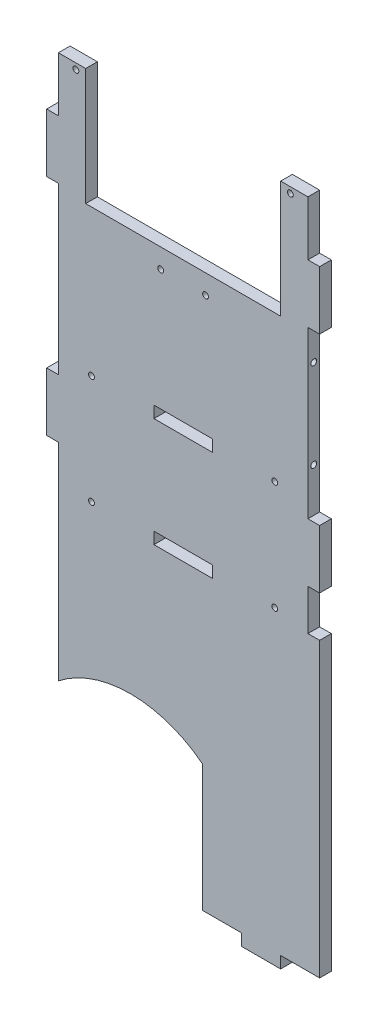
SolidWorks part; units mm, degrees
ref_plane "Plan de face" through (0, 0, 0) normal (0, 0, 1) x (1, 0, 0)
ref_plane "Plan de dessus" through (0, 0, 0) normal (0, 1, 0) x (1, 0, 0)
ref_plane "Plan de droite" through (0, 0, 0) normal (1, 0, 0) x (0, 0, -1)
sketch "Esquisse1" plane through (0, 0, 0) normal (0, 0, 1) x (1, 0, 0)
  line L0 (16.4964, 165.4872) -> (16.4964, 162.4872) construction
  line L1 (-0.0036, 165.4872) -> (139.9964, 165.4872)
  line L2 (-0.0036, 165.4872) -> (-0.0036, -184.5128)
  line L3 (-0.0036, -184.5128) -> (139.9964, -184.5128)
  line L4 (139.9964, 165.4872) -> (139.9964, -184.5128)
  line L5 (54.9964, -22.5128) -> (84.9964, -22.5128)
  line L6 (54.9964, -22.5128) -> (54.9964, -28.5128)
  line L7 (54.9964, -28.5128) -> (84.9964, -28.5128)
  line L8 (84.9964, -22.5128) -> (84.9964, -28.5128)
  line L9 (19.9964, 165.4872) -> (119.9964, 165.4872)
  line L11 (19.9964, 165.4872) -> (119.9964, 165.4872)
  line L12 (19.9964, 165.4872) -> (19.9964, 105.4872)
  line L13 (69.9964, 165.4872) -> (69.9964, -184.5128) construction
  line L18 (19.9964, 105.4872) -> (119.9964, 105.4872)
  line L19 (119.9964, 165.4872) -> (119.9964, 105.4872)
  circle A0 centre (14.9964, 162.4872) radius 1.5
  circle A1 centre (124.9964, 162.4872) radius 1.5
  circle A2 centre (69.9964, 162.3872) radius 3
  circle A5 centre (58.4964, 95.4872) radius 1.5
  circle A6 centre (22.9964, -25.5128) radius 1.5
  circle A7 centre (116.9964, -25.5128) radius 1.5
  circle A8 centre (81.4964, 95.4872) radius 1.5
  dimension "D3" = 3
  dimension "D6" = 60
  dimension "D9" = 10
  dimension "D23" = 11.5
  dimension "D24" = 3
  dimension "D25" = 3
  dimension "D27" = 3
  dimension "D28" = 3
  dimension "D1" = 140
  dimension "D2" = 350
  dimension "D4" = 15
  dimension "D5" = 15
  dimension "D7" = 100
  dimension "D8" = 5
  dimension "D11" = 3
  dimension "D12" = 23
  dimension "D13" = 23
  dimension "D14" = 156
  dimension "D15" = 6
  dimension "D16" = 55
  dimension "D17" = 30
  dimension "D29" = 3
  dimension "D31" = 3
sketch "Esquisse4" plane through (0, 0, 0) normal (0, 0, 1) x (1, 0, 0)
  line L0 (-0.0036, 165.4872) -> (-0.0036, -184.5128) construction
  line L1 (-0.0036, 165.4872) -> (5.9964, 165.4872)
  line L2 (-0.0036, 165.4872) -> (-0.0036, 137.4872)
  line L3 (-0.0036, 137.4872) -> (5.9964, 137.4872)
  line L4 (5.9964, 165.4872) -> (5.9964, 137.4872)
  line L5 (-0.0036, 107.4872) -> (5.9964, 107.4872)
  line L6 (-0.0036, 107.4872) -> (-0.0036, 22.4872)
  line L7 (-0.0036, 22.4872) -> (5.9964, 22.4872)
  line L8 (5.9964, 107.4872) -> (5.9964, 22.4872)
  line L9 (69.9964, 162.3872) -> (69.9964, -184.5128) construction
  line L10 (-0.0036, -7.5128) -> (5.9964, -7.5128)
  line L11 (-0.0036, -7.5128) -> (-0.0036, -58.5128)
  line L12 (-0.0036, -58.5128) -> (5.9964, -58.5128)
  line L13 (5.9964, -7.5128) -> (5.9964, -58.5128)
  line L14 (-0.0036, -184.5128) -> (139.9964, -184.5128) construction
  line L15 (139.9964, -7.5128) -> (133.9964, -7.5128)
  line L16 (133.9964, -7.5128) -> (133.9964, -28.5128)
  line L17 (133.9964, -28.5128) -> (139.9964, -28.5128)
  line L18 (139.9964, -28.5128) -> (139.9964, -7.5128)
  line L19 (139.9964, 22.4872) -> (133.9964, 22.4872)
  line L20 (139.9964, 107.4872) -> (139.9964, 22.4872)
  line L21 (133.9964, 107.4872) -> (133.9964, 22.4872)
  line L22 (139.9964, 107.4872) -> (133.9964, 107.4872)
  line L23 (139.9964, 165.4872) -> (133.9964, 165.4872)
  line L24 (139.9964, 137.4872) -> (133.9964, 137.4872)
  line L25 (139.9964, 165.4872) -> (139.9964, 137.4872)
  line L26 (133.9964, 165.4872) -> (133.9964, 137.4872)
  line L27 (139.9964, 165.4872) -> (139.9964, -222.3339) construction
  line L28 (190.2583, -184.5128) -> (43.4436, -184.5128) construction
  dimension "D1" = 6
  dimension "D2" = 28
  dimension "D3" = 30
  dimension "D4" = 85
  dimension "D5" = 30
  dimension "D6" = 51
  dimension "D7" = 21
  dimension "D8" = 30
  dimension "D9" = 6
extrude "Boss.-Extru.3" add sketch "Esquisse1" along normal blind 6
extrude "Enlèv. mat.-Extru.2" cut sketch "Esquisse4" along normal blind 6
sketch "Esquisse5" plane through (0, 0, 0) normal (1, 0, 0) x (0, 0, -1)
  line L0 (0, -125.6726) -> (0, 121.1593) construction
  line L1 (0, 121.1593) -> (0, 30.1192) construction
  line L2 (-6, -7.5128) -> (0, -7.5128) construction
  line L3 (-6, 22.4872) -> (0, 22.4872) construction
  line L4 (-6, 107.4872) -> (0, 107.4872) construction
  line L5 (-6, 137.4872) -> (0, 137.4872) construction
  circle A0 centre (-3, -30.0128) radius 1.5
  circle A1 centre (-3, -0.0128) radius 1.5
  circle A2 centre (-3, 90.4872) radius 1.5
  circle A3 centre (-3, 120.4872) radius 1.5
  point P5 (-3, -7.5128)
  point P11 (-3, 22.4872)
  point P20 (-3, 137.4872)
  dimension "D1" = 3
  dimension "D2" = 22.5
  dimension "D3" = 22.5
  dimension "D4" = 17
  dimension "D5" = 17
sketch "Esquisse6" plane through (133.9964, 0, 0) normal (1, 0, 0) x (0, 0, -1)
  line L0 (-6, 107.4872) -> (0, 107.4872) construction
  line L1 (-6, 107.4872) -> (-6, 22.4872) construction
  line L2 (-6, 22.4872) -> (0, 22.4872) construction
  line L3 (-3, 90.4872) -> (-3, 44.9872) construction
  line L5 (-6, 137.4872) -> (0, 137.4872) construction
  circle A0 centre (-3, 90.4872) radius 1.5
  circle A1 centre (-3, 44.9872) radius 1.5
  circle A3 centre (-3, 120.4872) radius 1.5
  point P8 (-3, 22.4872)
  point P17 (-3, 137.4872)
  dimension "D1" = 17
  dimension "D3" = 22.5
  dimension "D5" = 17
  dimension "D2" = 3
extrude "Enlèv. mat.-Extru.3" cut sketch "Esquisse5" along normal blind 9
extrude "Enlèv. mat.-Extru.6" cut sketch "Esquisse6" against normal blind 3
sketch "Esquisse7" plane through (0, 0, 0) normal (0, 0, 1) x (1, 0, 0)
  line L0 (-0.0036, -184.5128) -> (139.9964, -184.5128) construction
  line L1 (139.9964, -184.5128) -> (119.9964, -184.5128)
  line L2 (139.9964, -184.5128) -> (139.9964, -178.5128)
  line L3 (139.9964, -178.5128) -> (119.9964, -178.5128)
  line L4 (119.9964, -184.5128) -> (119.9964, -178.5128)
  line L5 (99.9964, -178.5128) -> (79.9964, -178.5128)
  line L6 (99.9964, -178.5128) -> (99.9964, -184.5128)
  line L7 (99.9964, -184.5128) -> (79.9964, -184.5128)
  line L8 (79.9964, -178.5128) -> (79.9964, -184.5128)
  dimension "D1" = 20
  dimension "D2" = 6
  dimension "D3" = 20
  dimension "D4" = 20
extrude "Enlèv. mat.-Extru.7" cut sketch "Esquisse7" along normal blind 10
sketch "Esquisse8" plane through (0, 0, 6) normal (0, 0, 1) x (1, 0, 0)
  line L0 (79.9964, -184.5128) -> (79.9964, -178.5128) construction
  line L2 (79.9964, -178.5128) -> (79.9964, -113.5128)
  line L3 (5.9964, -113.5128) -> (5.9964, -58.5128)
  line L4 (-0.0036, -184.5128) -> (79.9964, -184.5128) construction
  line L5 (5.9964, -184.5128) -> (5.9964, -58.5128) construction
  line L6 (5.9964, -58.5128) -> (-0.0036, -58.5128)
  line L8 (-0.0036, -58.5128) -> (-0.0036, -184.5128)
  line L9 (-0.0036, -184.5128) -> (79.9964, -184.5128)
  line L10 (79.9964, -184.5128) -> (79.9964, -178.5128)
  arc A1 (5.9964, -113.5128) -> (79.9964, -113.5128) centre (42.9964, -160.7463) cw
  dimension "D2" = 71
  dimension "D3" = 71
  dimension "D1" = 74
  dimension "D4" = 60
extrude "Enlèv. mat.-Extru.8" cut sketch "Esquisse8" against normal blind 6
sketch "Esquisse9" plane through (0, 0, 6) normal (0, 0, 1) x (1, 0, 0)
  line L0 (84.9964, 27.4872) -> (84.9964, 33.4872)
  line L1 (84.9964, 33.4872) -> (54.9964, 33.4872)
  line L2 (54.9964, 33.4872) -> (54.9964, 27.4872)
  line L3 (54.9964, 27.4872) -> (84.9964, 27.4872)
  line L4 (54.9964, -22.5128) -> (84.9964, -22.5128) construction
  line L5 (133.9964, 107.4872) -> (133.9964, 22.4872) construction
  line L6 (5.9964, 22.4872) -> (5.9964, 107.4872) construction
  circle A0 centre (116.9964, 30.4872) radius 1.5
  circle A1 centre (22.9964, 30.4872) radius 1.5
  circle A2 centre (22.9964, -25.5128) radius 1.5 construction
  circle A3 centre (116.9964, -25.5128) radius 1.5 construction
  dimension "D6" = 3
  dimension "D7" = 3
  dimension "D10" = 17
  dimension "D11" = 56
  dimension "D12" = 56
  dimension "D1" = 50
  dimension "D2" = 6
  dimension "D3" = 30
  dimension "D4" = 49
  dimension "D5" = 49
  dimension "D8" = 32
  dimension "D9" = 32
extrude "Enlèv. mat.-Extru.9" cut sketch "Esquisse9" against normal blind 6
